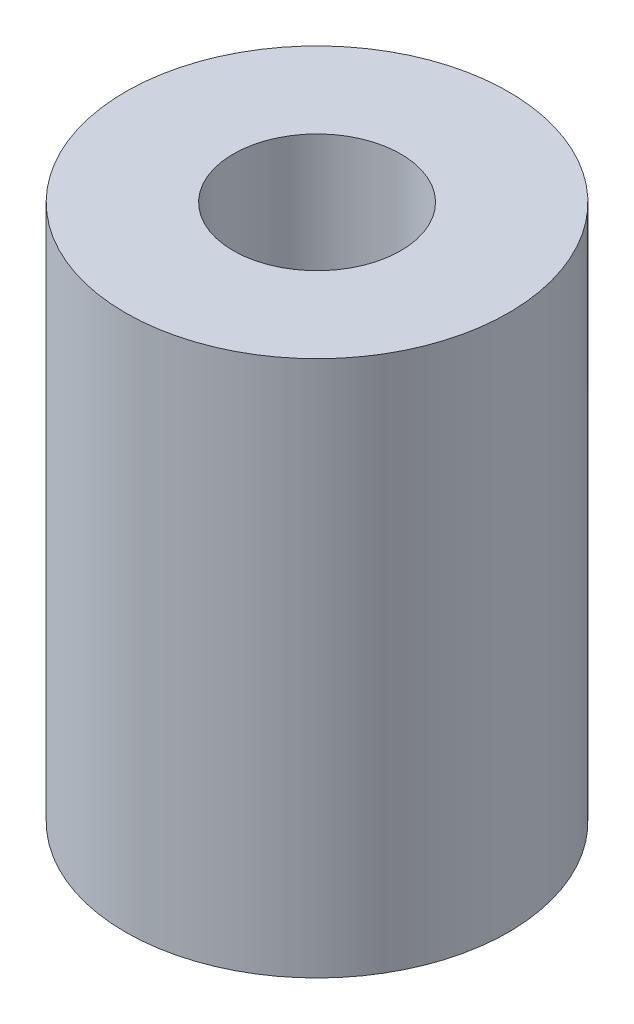
SolidWorks part; units mm, degrees
ref_plane "前视基准面" through (0, 0, 0) normal (0, 0, 1) x (1, 0, 0)
ref_plane "上视基准面" through (0, 0, 0) normal (0, 1, 0) x (1, 0, 0)
ref_plane "右视基准面" through (0, 0, 0) normal (1, 0, 0) x (0, 0, -1)
other "Configuration Table"
sketch "草图1" plane through (0, 0, 0) normal (0, 1, 0) x (1, 0, 0)
  circle A0 centre (0, 0) radius 1.75
  circle A1 centre (0, 0) radius 4
  dimension "D1" = 3.5
  dimension "D2" = 8
extrude "凸台-拉伸1" add sketch "草图1" along normal blind 11.2
